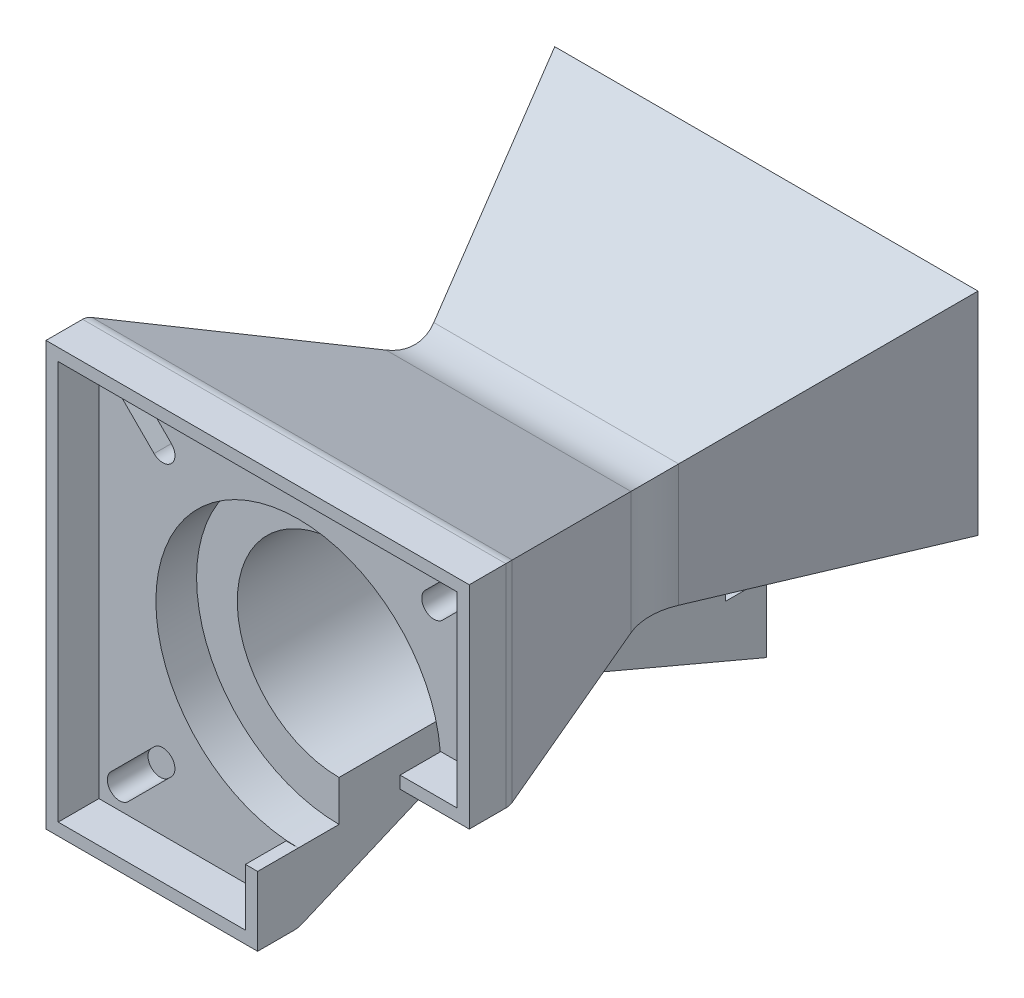
SolidWorks part; units mm, degrees
material "Cast Stainless Steel"
ref_plane "Front Plane" through (0, 0, 0) normal (0, 0, 1) x (1, 0, 0)
ref_plane "Top Plane" through (0, 0, 0) normal (0, 1, 0) x (1, 0, 0)
ref_plane "Right Plane" through (0, 0, 0) normal (1, 0, 0) x (0, 0, -1)
sketch "Sketch1" plane through (0, 0, 0) normal (0, 0, 1) x (1, 0, 0)
  line L1 (-52, -52) -> (52, -52)
  line L2 (-52, -52) -> (-52, 52)
  line L3 (-52, 52) -> (52, 52)
  line L4 (52, -52) -> (52, 52)
  line L5 (-52, -52) -> (52, 52) construction
  line L6 (-52, 52) -> (52, -52) construction
  point P0 (0, 0)
  dimension "D1" = 104
  dimension "D2" = 104
extrude "Boss-Extrude1" add sketch "Sketch1" along normal blind 57.5 draft 23
mirror "Mirror13" about plane through (0, 0, 57.5) normal (0, 0, -1) of bodies 101
sketch "Sketch2" plane through (0, 0, 115) normal (0, 0, 1) x (1, 0, 0)
  circle A0 centre (0, 0) radius 25
  dimension "D1" = 50
extrude "Cut-Extrude1" cut sketch "Sketch2" against normal through all
sketch "Sketch3" plane through (0, 0, 115) normal (0, 0, 1) x (1, 0, 0)
  circle A0 centre (0, 0) radius 35
  dimension "D1" = 70
extrude "Cut-Extrude2" cut sketch "Sketch3" against normal blind 10
sketch "Sketch4" plane through (0, 0, 0) normal (0, 0, -1) x (-1, 0, 0)
  circle A0 centre (0, 0) radius 35
  dimension "D1" = 70
extrude "Cut-Extrude3" cut sketch "Sketch4" against normal blind 10
fillet "Fillet1" radius 15 4 edges at (-27.5927, 0, 57.5) (0, 27.5927, 57.5) (27.5927, 0, 57.5) (0, -27.5927, 57.5)
sketch "Sketch6" plane through (0, 0, 115) normal (0, 0, 1) x (1, 0, 0)
  line L1 (0, 0) -> (52, 0)
  line L2 (0, 0) -> (0, -52)
  line L3 (0, -52) -> (52, -52)
  line L4 (52, 0) -> (52, -52)
extrude "Cut-Extrude4" cut sketch "Sketch6" against normal through all
sketch "Sketch7" plane through (0, 0, 115) normal (0, 0, 1) x (1, 0, 0)
  line L27 (49, 49) -> (49, 3)
  line L28 (49, 3) -> (35, 3)
  line L29 (-3, -35) -> (-3, -49)
  line L30 (-3, -49) -> (-49, -49)
  line L31 (-49, -49) -> (-49, 49)
  line L32 (-49, 49) -> (49, 49)
  line L33 (49, 49) -> (49, 3)
  line L34 (49, 3) -> (35, 3)
  line L35 (-3, -35) -> (-3, -49)
  line L36 (-3, -49) -> (-49, -49)
  line L37 (-49, -49) -> (-49, 49)
  line L38 (-49, 49) -> (49, 49)
  line L54 (-3, -35) -> (0, -35)
  line L55 (35, 3) -> (35, 0)
  line L60 (-52, -52) -> (-52, 52)
  line L61 (0, -52) -> (-52, -52)
  line L62 (0, -35) -> (0, -52)
  line L63 (52, 0) -> (35, 0)
  line L64 (52, 52) -> (52, 0)
  line L65 (-52, 52) -> (52, 52)
  line L66 (-52, -52) -> (-52, 52)
  line L67 (0, -52) -> (-52, -52)
  line L68 (0, -35) -> (0, -52)
  line L69 (52, 0) -> (35, 0)
  line L70 (52, 52) -> (52, 0)
  line L71 (-52, 52) -> (52, 52)
  dimension "D1" = 3
  dimension "D2" = 0
extrude "Boss-Extrude2" add sketch "Sketch7" along normal blind 10
sketch "Sketch8" plane through (0, 0, 115) normal (0, 0, 1) x (1, 0, 0)
  line L0 (0, 0) -> (-49, 49) construction
  line L1 (-49, -49) -> (49, 49) construction
  line L2 (-43.9269, 43.9269) -> (-33.3203, 33.3203) construction
  line L3 (-41.8056, 46.0482) -> (-31.199, 35.4416)
  line L4 (-46.0482, 41.8056) -> (-35.4416, 31.199)
  line L5 (43.9269, 43.9269) -> (33.3203, 33.3203) construction
  line L6 (46.0482, 41.8056) -> (35.4416, 31.199)
  line L7 (41.8056, 46.0482) -> (31.199, 35.4416)
  line L11 (-43.9269, -43.9269) -> (-33.3203, -33.3203) construction
  line L12 (-46.0482, -41.8056) -> (-35.4416, -31.199)
  line L13 (-41.8056, -46.0482) -> (-31.199, -35.4416)
  line L17 (43.9269, -43.9269) -> (33.3203, -33.3203) construction
  line L18 (41.8056, -46.0482) -> (31.199, -35.4416)
  line L19 (46.0482, -41.8056) -> (35.4416, -31.199)
  line L20 (43.9269, -43.9269) -> (33.3203, -33.3203) construction
  line L21 (41.8056, -46.0482) -> (31.199, -35.4416)
  line L22 (46.0482, -41.8056) -> (35.4416, -31.199)
  arc A0 (-41.8056, 46.0482) -> (-46.0482, 41.8056) centre (-43.9269, 43.9269) ccw
  arc A1 (-35.4416, 31.199) -> (-31.199, 35.4416) centre (-33.3203, 33.3203) ccw
  arc A2 (46.0482, 41.8056) -> (41.8056, 46.0482) centre (43.9269, 43.9269) ccw
  arc A3 (31.199, 35.4416) -> (35.4416, 31.199) centre (33.3203, 33.3203) ccw
  arc A6 (-46.0482, -41.8056) -> (-41.8056, -46.0482) centre (-43.9269, -43.9269) ccw
  arc A7 (-31.199, -35.4416) -> (-35.4416, -31.199) centre (-33.3203, -33.3203) ccw
  arc A12 (41.8056, -46.0482) -> (46.0482, -41.8056) centre (43.9269, -43.9269) ccw
  arc A13 (35.4416, -31.199) -> (31.199, -35.4416) centre (33.3203, -33.3203) ccw
  point P8 (0, 0)
  point P10 (-38.6236, 38.6236)
  point P15 (-37.0866, -44.534)
  point P20 (38.6236, 38.6236)
  point P34 (-38.6236, -38.6236)
  point P39 (0, 0)
  point P40 (38.6236, -38.6236)
  point P47 (38.6236, -38.6236)
  point P54 (38.6236, -38.6236)
  dimension "D2" = 3
  dimension "D1" = 15
  dimension "D3" = 4
extrude "Cut-Extrude5" cut sketch "Sketch8" against normal blind 10
fillet "Fillet2" radius 5 4 edges at (-26, -52, 115) (-52, 0, 115) (0, 52, 115) (52, 26, 115)
equation "\"A\"= 115mm"
equation "\"B\" = 104mm"
equation "\"C\"= 23deg"
equation "\"D1@Boss-Extrude1\"=\"A\"/2"
